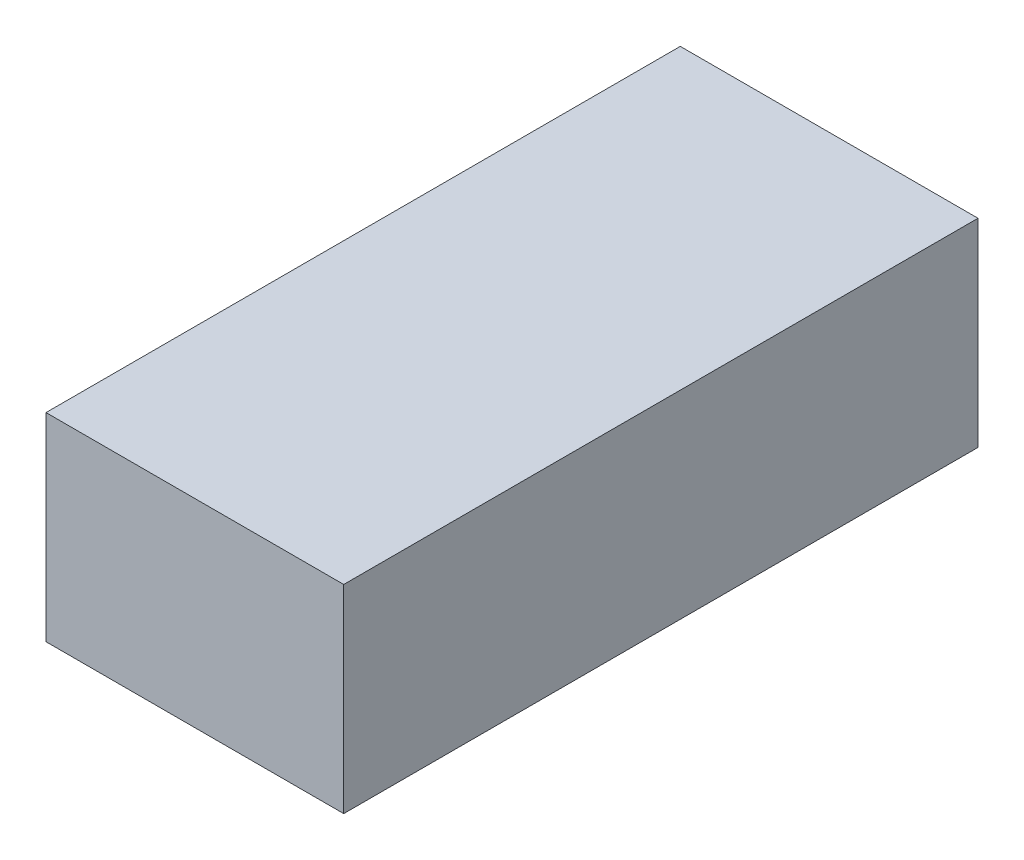
SolidWorks part; units mm, degrees
ref_plane "Front Plane" through (0, 0, 0) normal (0, 0, 1) x (1, 0, 0)
ref_plane "Top Plane" through (0, 0, 0) normal (0, 1, 0) x (1, 0, 0)
ref_plane "Right Plane" through (0, 0, 0) normal (1, 0, 0) x (0, 0, -1)
sketch "Sketch1" plane through (0, 0, 0) normal (0, 0, 1) x (1, 0, 0)
  line L1 (-17.25, -11.5) -> (17.25, -11.5)
  line L2 (-17.25, -11.5) -> (-17.25, 11.5)
  line L3 (-17.25, 11.5) -> (17.25, 11.5)
  line L4 (17.25, -11.5) -> (17.25, 11.5)
  line L5 (-17.25, -11.5) -> (17.25, 11.5) construction
  line L6 (-17.25, 11.5) -> (17.25, -11.5) construction
  point P0 (0, 0)
  dimension "D1" = 23
  dimension "D2" = 34.5001
extrude "Boss-Extrude1" add sketch "Sketch1" along normal mid plane 73.5
equation "\"D2@Sketch1\"=\"Batt X@Quad Assemb.sldasm\""
equation "\"D1@Sketch1\"=\"Batt Z@Quad Assemb.sldasm\""
equation "\"D1@Boss-Extrude1\"=\"Batt Y@Quad Assemb.sldasm\""
